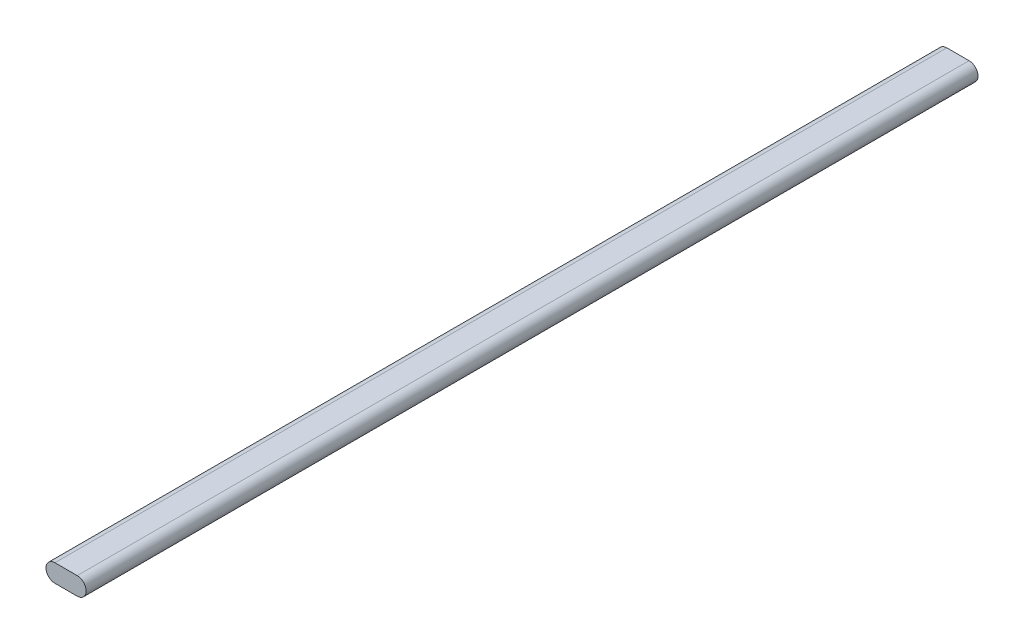
SolidWorks part; units mm, degrees
ref_plane "Płaszczyzna przednia" through (0, 0, 0) normal (0, 0, 1) x (1, 0, 0)
ref_plane "Płaszczyzna górna" through (0, 0, 0) normal (0, 1, 0) x (1, 0, 0)
ref_plane "Płaszczyzna prawa" through (0, 0, 0) normal (1, 0, 0) x (0, 0, -1)
sketch "Szkic1" plane through (0, 0, 0) normal (0, 0, 1) x (1, 0, 0)
  line L0 (0, 0) -> (0.25, 0) construction
  line L1 (0, 0.1) -> (0.25, 0.1)
  line L2 (0, -0.1) -> (0.25, -0.1)
  line L3 (-0.1, 0) -> (0.35, 0)
  line L4 (0.125, -0.1) -> (0.125, 0.1)
  arc A0 (0, 0.1) -> (0, -0.1) centre (0, 0) ccw
  arc A1 (0.25, -0.1) -> (0.25, 0.1) centre (0.25, 0) ccw
  point P3 (0.125, 0)
  dimension "D2" = 0.45
  dimension "D1" = 0.2
extrude "Dodanie-wyciągnięcie1" add sketch "Szkic1" along normal blind 10 contours L3 A1 L1 L4 | L2 A1 L3 L4 | L1 A0 L3 L4 | L3 A0 L2 L4
